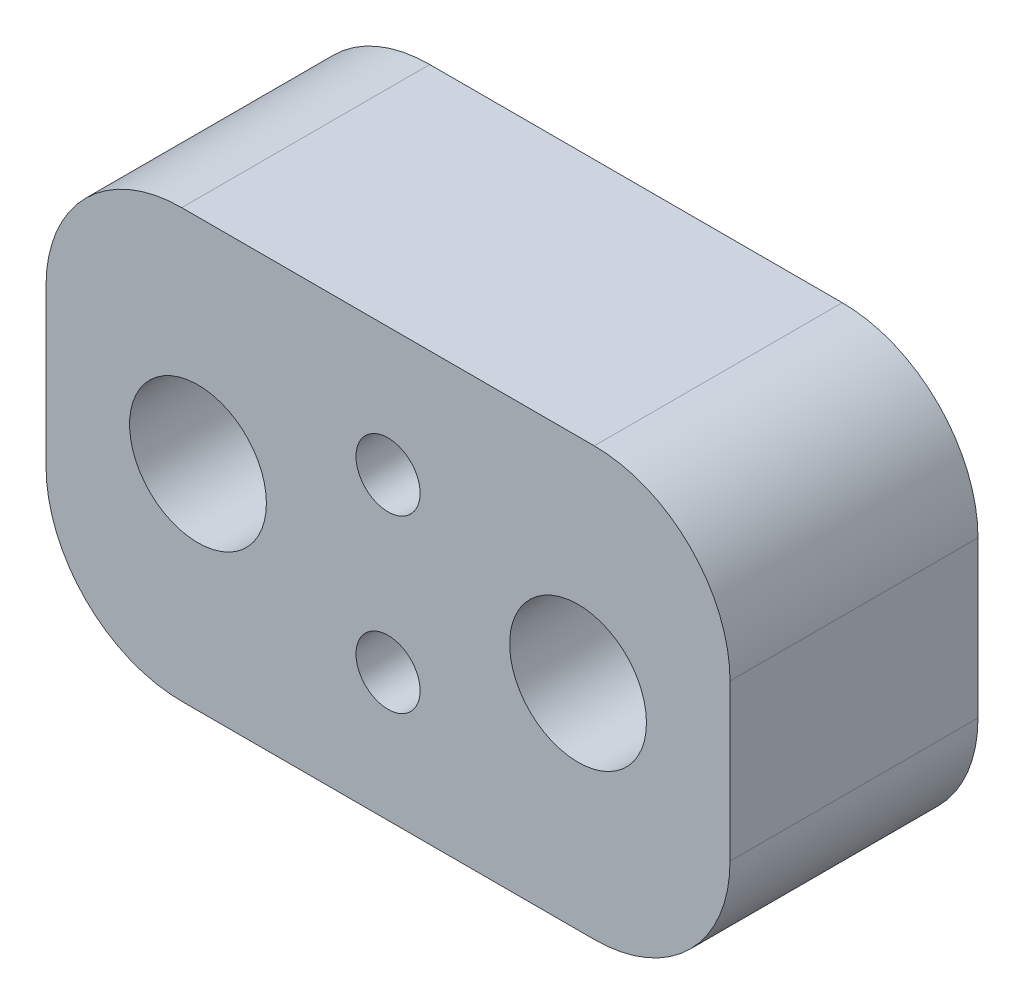
SolidWorks part; units mm, degrees
material "ABS PC"
ref_plane "Front Plane" through (0, 0, 0) normal (0, 0, 1) x (1, 0, 0)
ref_plane "Top Plane" through (0, 0, 0) normal (0, 1, 0) x (1, 0, 0)
ref_plane "Right Plane" through (0, 0, 0) normal (1, 0, 0) x (0, 0, -1)
sketch "Sketch1" plane through (0, 0, 0) normal (0, 0, 1) x (1, 0, 0)
  line L1 (0, 0) -> (16, 0)
  line L2 (0, 0) -> (0, 10)
  line L3 (0, 10) -> (16, 10)
  line L4 (16, 0) -> (16, 10)
  dimension "D1" = 16
  dimension "D2" = 10
extrude "Boss-Extrude1" add sketch "Sketch1" along normal blind 5.8
sketch "Sketch2" plane through (0, 0, 5.8) normal (0, 0, 1) x (1, 0, 0)
  line L0 (8, 10) -> (8, 0) construction
  line L1 (16, 10) -> (0, 10) construction
  line L2 (0, 0) -> (16, 0) construction
  circle A0 centre (8, 7) radius 0.75
  circle A1 centre (8, 3) radius 0.75
  dimension "D1" = 1.5
  dimension "D2" = 3
  dimension "D3" = 4
extrude "Cut-Extrude1" cut sketch "Sketch2" against normal blind 5.8
hole_wizard "M3 Clearance Hole1" positions "Sketch4" profile "Sketch3" hole size "M3" standard "Ansi Metric"
sketch "Sketch4" plane through (0, 0, 5.8) normal (0, 0, 1) x (1, 0, 0)
  line L0 (3.555, 5) -> (8, 5) construction
  line L2 (8, 5) -> (12.445, 5) construction
  line L4 (3.555, 5) -> (0, 5) construction
  line L7 (12.445, 5) -> (16, 5) construction
  line L9 (16, 0) -> (16, 10) construction
  line L10 (0, 10) -> (0, 0) construction
  point P0 (3.555, 5)
  point P1 (12.445, 5)
  dimension "D1" = 8.89
sketch "Sketch3" plane through (3.555, 5, 5.8) normal (1, 0, 0) x (0, -1, 0)
  line L0 (0, 0) -> (0, 37.2414)
  line L1 (0, 37.2414) -> (1.6, 36.28)
  line L2 (1.6, 36.28) -> (1.6, 0)
  line L5 (1.6, 0) -> (0, 0)
  line L10 (0, 37.2414) -> (-1.6, 36.28) construction
  line L11 (0, -6.35) -> (0, 107.95) construction
  dimension "Hole Dia." = 3.2
  dimension "Hole Depth" = 36.28
  dimension "Drill Angle" = 118
fillet "Fillet1" radius 3.175 4 edges at (0, 0, 2.9) (16, 0, 2.9) (16, 10, 2.9) (0, 10, 2.9)
